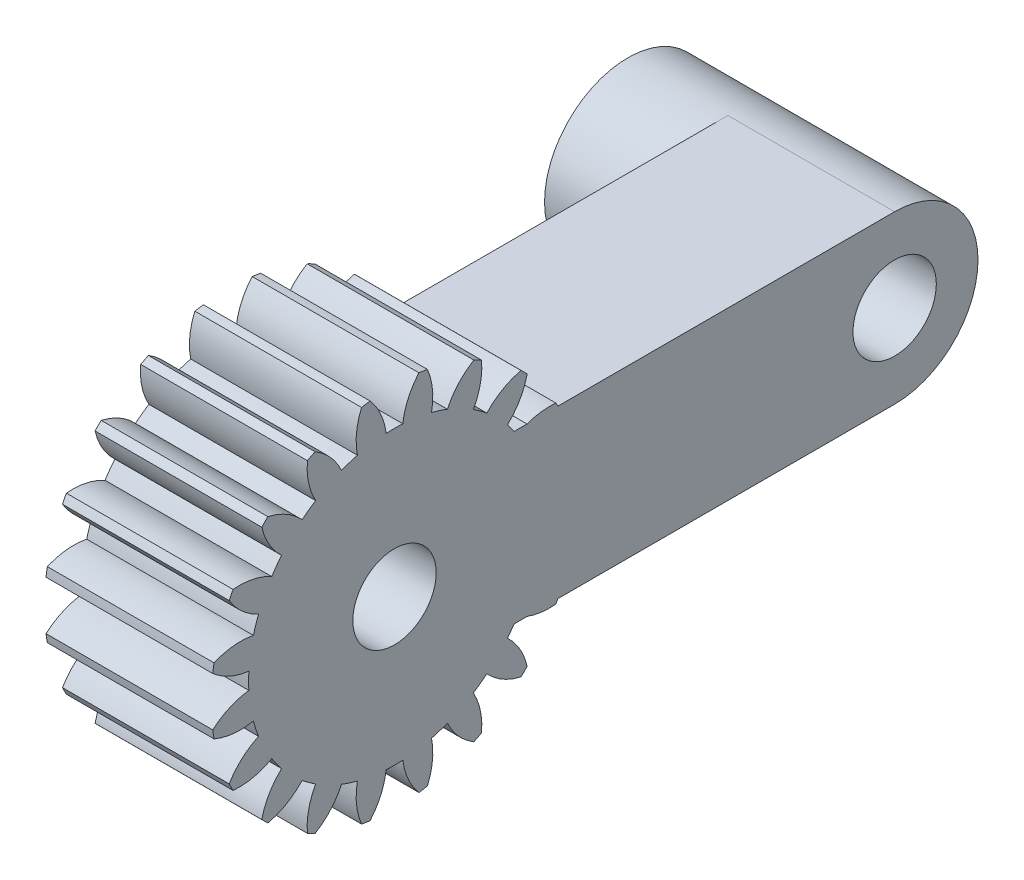
SolidWorks part; units mm, degrees
ref_plane "Front Plane" through (0, 0, 0) normal (0, 0, 1) x (1, 0, 0)
ref_plane "Top Plane" through (0, 0, 0) normal (0, 1, 0) x (1, 0, 0)
ref_plane "Right Plane" through (0, 0, 0) normal (1, 0, 0) x (0, 0, -1)
ref_plane "Plane1" through (4.0439, 0, 0) normal (1, 0, 0) x (0, 0, -1)
sketch "Sketch1" plane through (4.0439, 0, 0) normal (1, 0, 0) x (0, 0, -1)
  circle A0 centre (0.8725, -1.1221) radius 2.5
  arc A1 (-10.0295, 0.3429) -> (-7.8622, -0.6222) centre (-7.392, 3.3501) ccw
  arc A2 (-7.8622, -0.6222) -> (-7.8622, -1.622) centre (0.8725, -1.1221) ccw
  arc A3 (-7.8622, -1.622) -> (-10.0295, -2.587) centre (-7.392, -5.5943) ccw
  arc A4 (-10.0295, -2.587) -> (-9.9487, -3.0977) centre (0.8725, -1.1221) ccw
  arc A5 (-9.9487, -3.0977) -> (-7.5892, -3.3458) centre (-8.3695, 0.5774) ccw
  arc A6 (-7.5892, -3.3458) -> (-7.2802, -4.2967) centre (0.8725, -1.1221) ccw
  arc A7 (-7.2802, -4.2967) -> (-9.0433, -5.8842) centre (-5.6055, -7.9292) ccw
  arc A8 (-9.0433, -5.8842) -> (-8.8085, -6.3449) centre (0.8725, -1.1221) ccw
  arc A9 (-8.8085, -6.3449) -> (-6.4879, -5.8518) centre (-8.4423, -2.3617) ccw
  arc A10 (-6.4879, -5.8518) -> (-5.9002, -6.6607) centre (0.8725, -1.1221) ccw
  arc A11 (-5.9002, -6.6607) -> (-7.0864, -8.7153) centre (-3.185, -9.5979) ccw
  arc A12 (-7.0864, -8.7153) -> (-6.7207, -9.0809) centre (0.8725, -1.1221) ccw
  arc A13 (-6.7207, -9.0809) -> (-4.6661, -7.8948) centre (-7.6033, -5.1795) ccw
  arc A14 (-4.6661, -7.8948) -> (-3.8572, -8.4825) centre (0.8725, -1.1221) ccw
  arc A15 (-3.8572, -8.4825) -> (-4.3504, -10.8031) centre (-0.3672, -10.4369) ccw
  arc A16 (-4.3504, -10.8031) -> (-3.8897, -11.0378) centre (0.8725, -1.1221) ccw
  arc A17 (-3.8897, -11.0378) -> (-2.3022, -9.2748) centre (-5.9347, -7.6001) ccw
  arc A18 (-2.3022, -9.2748) -> (-1.3512, -9.5838) centre (0.8725, -1.1221) ccw
  arc A19 (-1.3512, -9.5838) -> (-1.1032, -11.9432) centre (2.5719, -10.3641) ccw
  arc A20 (-1.1032, -11.9432) -> (-0.5925, -12.0241) centre (0.8725, -1.1221) ccw
  arc A21 (-0.5925, -12.0241) -> (0.3725, -9.8568) centre (-3.5997, -9.3866) ccw
  arc A22 (0.3725, -9.8568) -> (1.3724, -9.8568) centre (0.8725, -1.1221) ccw
  arc A23 (1.3724, -9.8568) -> (2.3374, -12.0241) centre (5.3447, -9.3866) ccw
  arc A24 (2.3374, -12.0241) -> (2.8481, -11.9432) centre (0.8725, -1.1221) ccw
  arc A25 (2.8481, -11.9432) -> (3.0962, -9.5838) centre (-0.827, -10.3641) ccw
  arc A26 (3.0962, -9.5838) -> (4.0471, -9.2748) centre (0.8725, -1.1221) ccw
  arc A27 (4.0471, -9.2748) -> (5.6346, -11.0378) centre (7.6796, -7.6001) ccw
  arc A28 (5.6346, -11.0378) -> (6.0953, -10.8031) centre (0.8725, -1.1221) ccw
  arc A29 (6.0953, -10.8031) -> (5.6022, -8.4825) centre (2.1121, -10.4369) ccw
  arc A30 (5.6022, -8.4825) -> (6.411, -7.8948) centre (0.8725, -1.1221) ccw
  arc A31 (6.411, -7.8948) -> (8.4657, -9.0809) centre (9.3483, -5.1795) ccw
  arc A32 (8.4657, -9.0809) -> (8.8313, -8.7153) centre (0.8725, -1.1221) ccw
  arc A33 (8.8313, -8.7153) -> (7.6451, -6.6607) centre (4.9299, -9.5979) ccw
  arc A34 (7.6451, -6.6607) -> (8.2328, -5.8518) centre (0.8725, -1.1221) ccw
  arc A35 (8.2328, -5.8518) -> (10.5535, -6.3449) centre (10.1873, -2.3617) ccw
  arc A36 (10.5535, -6.3449) -> (10.7882, -5.8842) centre (0.8725, -1.1221) ccw
  arc A37 (10.7882, -5.8842) -> (9.0252, -4.2967) centre (7.3505, -7.9292) ccw
  arc A38 (9.0252, -4.2967) -> (9.3342, -3.3458) centre (0.8725, -1.1221) ccw
  arc A39 (9.3342, -3.3458) -> (11.6936, -3.0977) centre (10.1144, 0.5774) ccw
  arc A40 (11.6936, -3.0977) -> (11.7745, -2.587) centre (0.8725, -1.1221) ccw
  arc A41 (11.7745, -2.587) -> (9.6072, -1.622) centre (9.137, -5.5943) ccw
  arc A42 (9.6072, -1.622) -> (9.6072, -0.6222) centre (0.8725, -1.1221) ccw
  arc A43 (9.6072, -0.6222) -> (11.7745, 0.3429) centre (9.137, 3.3501) ccw
  arc A44 (11.7745, 0.3429) -> (11.6936, 0.8536) centre (0.8725, -1.1221) ccw
  arc A45 (11.6936, 0.8536) -> (9.3342, 1.1016) centre (10.1144, -2.8215) ccw
  arc A46 (9.3342, 1.1016) -> (9.0252, 2.0526) centre (0.8725, -1.1221) ccw
  arc A47 (9.0252, 2.0526) -> (10.7882, 3.6401) centre (7.3505, 5.6851) ccw
  arc A48 (10.7882, 3.6401) -> (10.5535, 4.1008) centre (0.8725, -1.1221) ccw
  arc A49 (10.5535, 4.1008) -> (8.2328, 3.6076) centre (10.1873, 0.1176) ccw
  arc A50 (8.2328, 3.6076) -> (7.6451, 4.4165) centre (0.8725, -1.1221) ccw
  arc A51 (7.6451, 4.4165) -> (8.8313, 6.4711) centre (4.9299, 7.3537) ccw
  arc A52 (8.8313, 6.4711) -> (8.4657, 6.8368) centre (0.8725, -1.1221) ccw
  arc A53 (8.4657, 6.8368) -> (6.411, 5.6506) centre (9.3483, 2.9353) ccw
  arc A54 (6.411, 5.6506) -> (5.6022, 6.2383) centre (0.8725, -1.1221) ccw
  arc A55 (5.6022, 6.2383) -> (6.0953, 8.5589) centre (2.1121, 8.1927) ccw
  arc A56 (6.0953, 8.5589) -> (5.6346, 8.7937) centre (0.8725, -1.1221) ccw
  arc A57 (5.6346, 8.7937) -> (4.0471, 7.0306) centre (7.6796, 5.3559) ccw
  arc A58 (4.0471, 7.0306) -> (3.0962, 7.3396) centre (0.8725, -1.1221) ccw
  arc A59 (3.0962, 7.3396) -> (2.8481, 9.6991) centre (-0.827, 8.1199) ccw
  arc A60 (2.8481, 9.6991) -> (2.3374, 9.7799) centre (0.8725, -1.1221) ccw
  arc A61 (2.3374, 9.7799) -> (1.3724, 7.6126) centre (5.3447, 7.1424) ccw
  arc A62 (1.3724, 7.6126) -> (0.3725, 7.6126) centre (0.8725, -1.1221) ccw
  arc A63 (0.3725, 7.6126) -> (-0.5925, 9.7799) centre (-3.5997, 7.1424) ccw
  arc A64 (-0.5925, 9.7799) -> (-1.1032, 9.6991) centre (0.8725, -1.1221) ccw
  arc A65 (-1.1032, 9.6991) -> (-1.3512, 7.3396) centre (2.5719, 8.1199) ccw
  arc A66 (-1.3512, 7.3396) -> (-2.3022, 7.0306) centre (0.8725, -1.1221) ccw
  arc A67 (-2.3022, 7.0306) -> (-3.8897, 8.7937) centre (-5.9347, 5.3559) ccw
  arc A68 (-3.8897, 8.7937) -> (-4.3504, 8.5589) centre (0.8725, -1.1221) ccw
  arc A69 (-4.3504, 8.5589) -> (-3.8572, 6.2383) centre (-0.3672, 8.1927) ccw
  arc A70 (-3.8572, 6.2383) -> (-4.6661, 5.6506) centre (0.8725, -1.1221) ccw
  arc A71 (-4.6661, 5.6506) -> (-6.7207, 6.8368) centre (-7.6033, 2.9353) ccw
  arc A72 (-6.7207, 6.8368) -> (-7.0864, 6.4711) centre (0.8725, -1.1221) ccw
  arc A73 (-7.0864, 6.4711) -> (-5.9002, 4.4165) centre (-3.185, 7.3537) ccw
  arc A74 (-5.9002, 4.4165) -> (-6.4879, 3.6076) centre (0.8725, -1.1221) ccw
  arc A75 (-6.4879, 3.6076) -> (-8.8085, 4.1008) centre (-8.4423, 0.1176) ccw
  arc A76 (-8.8085, 4.1008) -> (-9.0433, 3.6401) centre (0.8725, -1.1221) ccw
  arc A77 (-9.0433, 3.6401) -> (-7.2802, 2.0526) centre (-5.6055, 5.6851) ccw
  arc A78 (-7.2802, 2.0526) -> (-7.5892, 1.1016) centre (0.8725, -1.1221) ccw
  arc A79 (-7.5892, 1.1016) -> (-9.9487, 0.8536) centre (-8.3695, -2.8215) ccw
  arc A80 (-9.9487, 0.8536) -> (-10.0295, 0.3429) centre (0.8725, -1.1221) ccw
extrude "Boss-Extrude1" add sketch "Sketch1" against normal blind 10
sketch "Sketch2" plane through (4.0439, 0, 0) normal (1, 0, 0) x (0, 0, -1)
  line L0 (0.8725, -1.1221) -> (30.8725, -1.1221) construction
  line L1 (0.8725, 3.8779) -> (30.8725, 3.8779)
  line L2 (0.8725, -6.1221) -> (30.8725, -6.1221)
  arc A0 (0.8725, 3.8779) -> (0.8725, -6.1221) centre (0.8725, -1.1221) ccw
  arc A1 (30.8725, -6.1221) -> (30.8725, 3.8779) centre (30.8725, -1.1221) ccw
  arc A2 (35.8678, -1.3374) -> (35.8678, -0.9067) centre (30.8725, -1.1221) ccw
  circle A3 centre (30.8725, -1.1221) radius 2.5
  point P3 (15.8725, -1.1221)
  dimension "D2" = 5
  dimension "D1" = 10
  dimension "D3" = 30
extrude "Boss-Extrude2" add sketch "Sketch2" against normal blind 10
sketch "Sketch3" plane through (-5.9561, 0, 0) normal (-1, 0, 0) x (0, 0, 1)
  circle A0 centre (-30.8725, -1.1221) radius 2.5
  circle A1 centre (-30.8725, -1.1221) radius 5
extrude "Boss-Extrude3" add sketch "Sketch3" along normal blind 6
sketch "Sketch4" plane through (4.0439, 0, 0) normal (1, 0, 0) x (0, 0, -1)
  circle A1 centre (0.8725, -1.1221) radius 2.5
  dimension "D1" = 5
extrude "Cut-Extrude1" cut sketch "Sketch4" against normal blind 6
